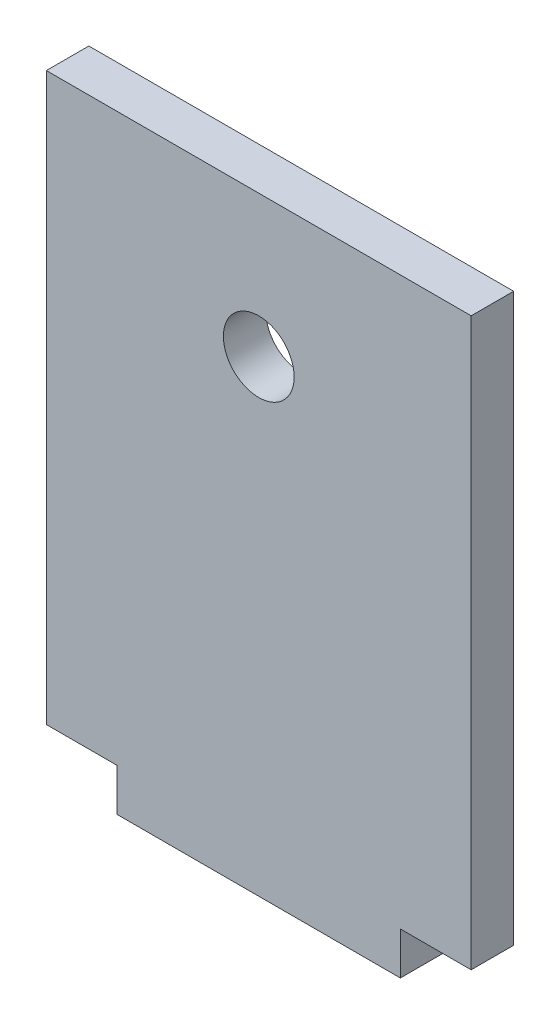
SolidWorks part; units mm, degrees
ref_plane "Front Plane" through (0, 0, 0) normal (0, 0, 1) x (1, 0, 0)
ref_plane "Top Plane" through (0, 0, 0) normal (0, 1, 0) x (1, 0, 0)
ref_plane "Right Plane" through (0, 0, 0) normal (1, 0, 0) x (0, 0, -1)
sketch "Sketch1" plane through (0, 0, 0) normal (0, 0, 1) x (1, 0, 0)
  line L0 (-10, -20) -> (-10, -23)
  line L1 (15, -20) -> (10, -20)
  line L2 (15, -20) -> (15, 20)
  line L3 (15, 20) -> (-15, 20)
  line L4 (-15, -20) -> (-15, 20)
  line L5 (15, -20) -> (-15, 20) construction
  line L6 (15, 20) -> (-15, -20) construction
  line L7 (-10, -23) -> (10, -23)
  line L8 (10, -23) -> (10, -20)
  line L9 (-10, -20) -> (-15, -20)
  circle A0 centre (0, 10) radius 2.5
  point P0 (0, 0)
  dimension "D7" = 5
  dimension "D1" = 30
  dimension "D2" = 40
  dimension "D3" = 5
  dimension "D4" = 20
  dimension "D5" = 3
  dimension "D6" = 10
extrude "Boss-Extrude1" add sketch "Sketch1" along normal blind 3
